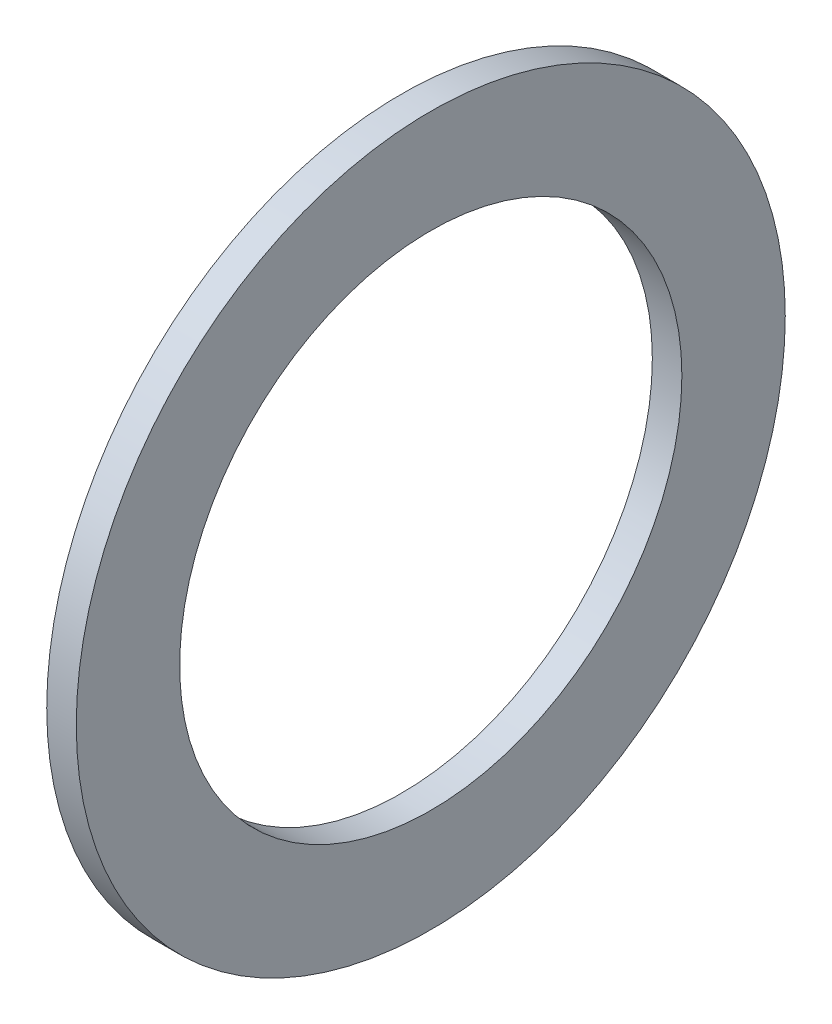
SolidWorks part; units mm, degrees
material "Stainless Steel (ferritic)"
ref_plane "X-Y Datum" through (0, 0, 0) normal (0, 0, 1) x (1, 0, 0)
ref_plane "X-Z Datum" through (0, 0, 0) normal (0, 1, 0) x (1, 0, 0)
ref_plane "Y-Z Datum" through (0, 0, 0) normal (1, 0, 0) x (0, 0, -1)
sketch "Sketch1" plane through (0, 0, 0) normal (1, 0, 0) x (0, 0, -1)
  circle A0 centre (0, 0) radius 12
  circle A1 centre (0, 0) radius 8.5
  dimension "D1" = 24
  dimension "D2" = 17
extrude "Boss-Extrude1" add sketch "Sketch1" along normal blind 1
